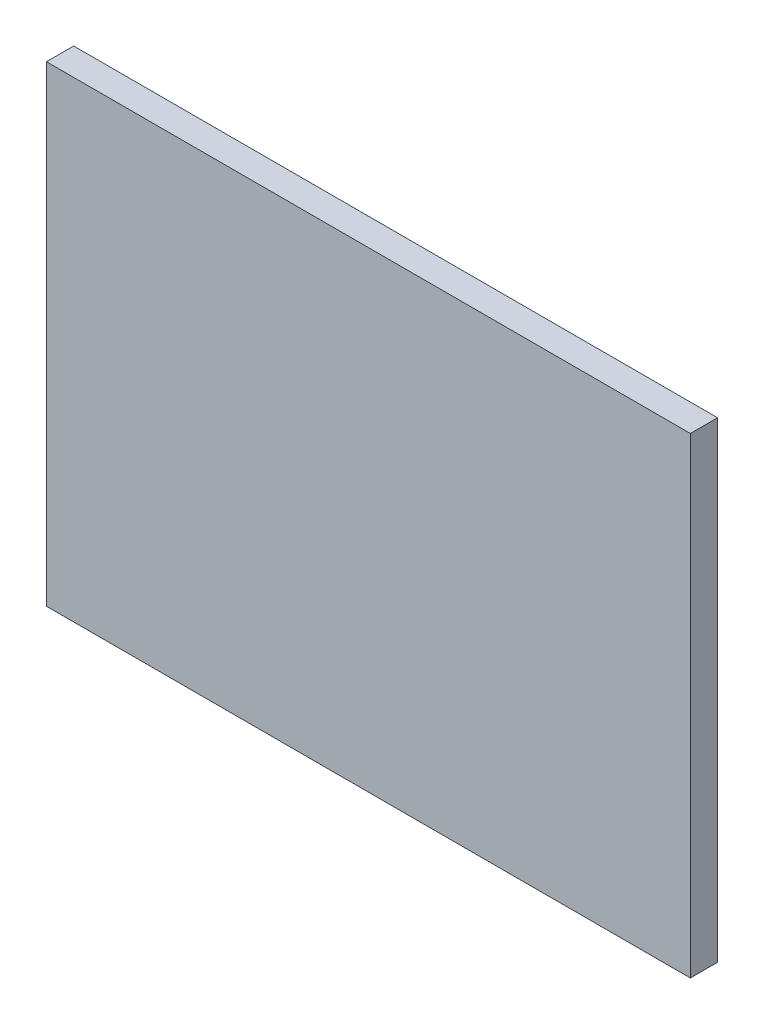
SolidWorks part; units mm, degrees
ref_plane "前视基准面" through (0, 0, 0) normal (0, 0, 1) x (1, 0, 0)
ref_plane "上视基准面" through (0, 0, 0) normal (0, 1, 0) x (1, 0, 0)
ref_plane "右视基准面" through (0, 0, 0) normal (1, 0, 0) x (0, 0, -1)
sketch "草图1" plane through (0, 0, 0) normal (0, 0, 1) x (1, 0, 0)
  line L1 (-35.5, -26) -> (35.5, -26)
  line L2 (-35.5, -26) -> (-35.5, 26)
  line L3 (-35.5, 26) -> (35.5, 26)
  line L4 (35.5, -26) -> (35.5, 26)
  line L5 (-35.5, -26) -> (35.5, 26) construction
  line L6 (-35.5, 26) -> (35.5, -26) construction
  point P0 (0, 0)
  dimension "D1" = 71
  dimension "D2" = 52
extrude "凸台-拉伸1" add sketch "草图1" along normal blind 3
